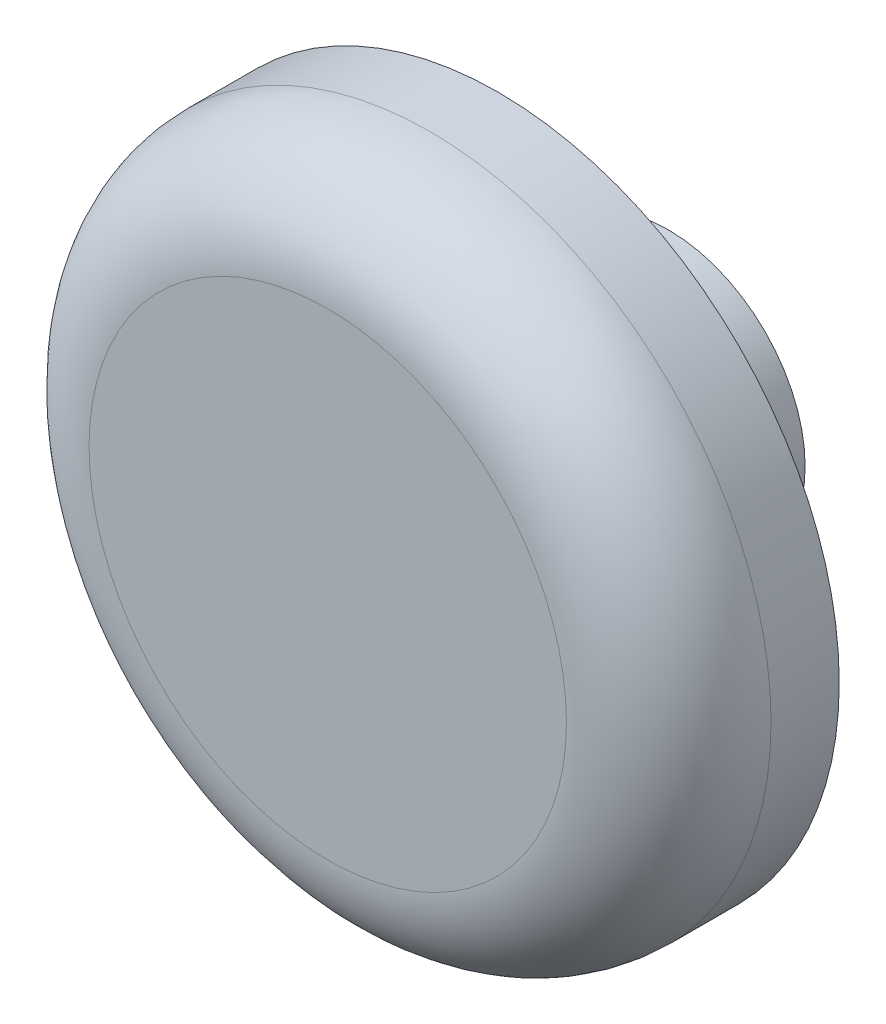
SolidWorks part; units mm, degrees
ref_plane "Front Plane" through (0, 0, 0) normal (0, 0, 1) x (1, 0, 0)
ref_plane "Top Plane" through (0, 0, 0) normal (0, 1, 0) x (1, 0, 0)
ref_plane "Right Plane" through (0, 0, 0) normal (1, 0, 0) x (0, 0, -1)
sketch "Sketch1" plane through (0, 0, 0) normal (0, 1, 0) x (1, 0, 0)
  line L0 (4, 0) -> (0, 0)
  line L1 (0, 0) -> (0, -10)
  line L2 (0, -10) -> (7, -10)
  line L3 (10, -7) -> (10, -5)
  line L4 (10, -5) -> (4, -5)
  line L5 (4, -5) -> (4, 0)
  line L6 (0, 0) -> (0, -10.0013) construction
  arc A0 (7, -10) -> (10, -7) centre (7, -7) ccw
revolve "Revolve1" add sketch "Sketch1" angle 360 about L6
